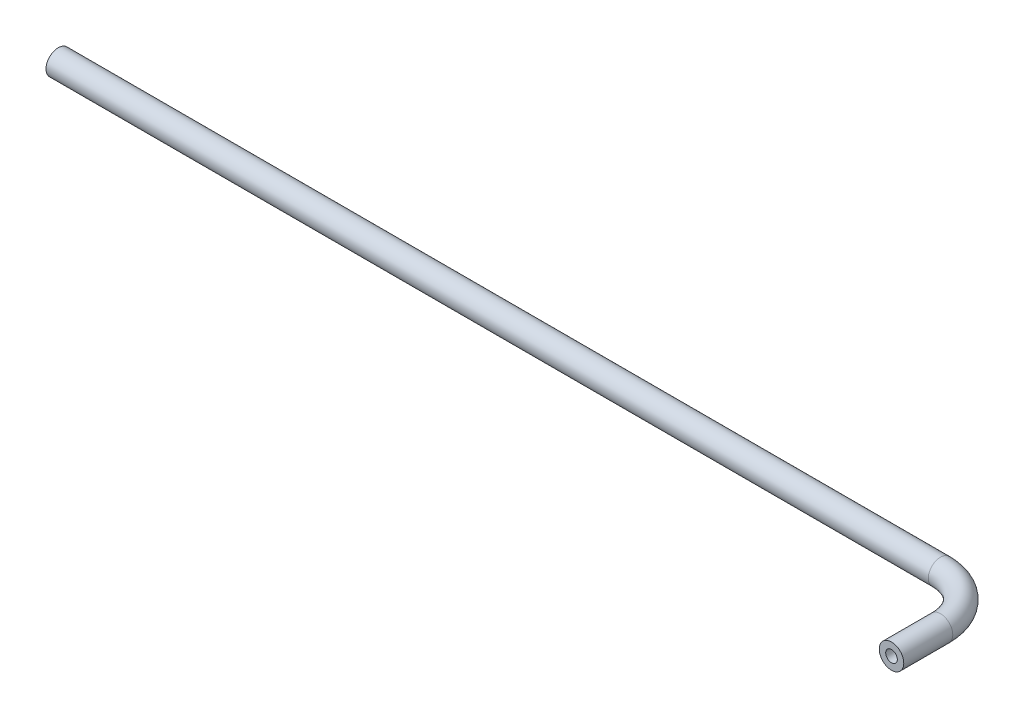
SolidWorks part; units mm, degrees
material "6061 Alloy"
ref_plane "Front Plane" through (0, 0, 0) normal (0, 0, 1) x (1, 0, 0)
ref_plane "Top Plane" through (0, 0, 0) normal (0, 1, 0) x (1, 0, 0)
ref_plane "Right Plane" through (0, 0, 0) normal (1, 0, 0) x (0, 0, -1)
sketch "Sketch1" plane through (0, 0, 0) normal (0, 1, 0) x (1, 0, 0)
  line L0 (-241.3, 0) -> (-12.7, 0)
  line L1 (-55, 0) -> (55, 0) construction
  line L2 (0, -12.7) -> (0, -25.4)
  line L3 (0, -55) -> (0, 55) construction
  arc A0 (0, -12.7) -> (-12.7, 0) centre (-12.7, -12.7) ccw
  dimension "D3" = 25.4
  dimension "D1" = 228.6
  dimension "D2" = 12.7
ref_plane "Plane1" through (-241.3, 0, 0) normal (1, 0, 0) x (0, 0, -1)
sketch "Sketch2" plane through (-241.3, 0, 0) normal (1, 0, 0) x (0, 0, -1)
  circle A0 centre (0, 0) radius 3.175
  circle A1 centre (0, 0) radius 1.5
  dimension "D1" = 6.35
  dimension "D2" = 3
sweep "Sweep1" add profiles "Sketch2" path "Sketch1"
